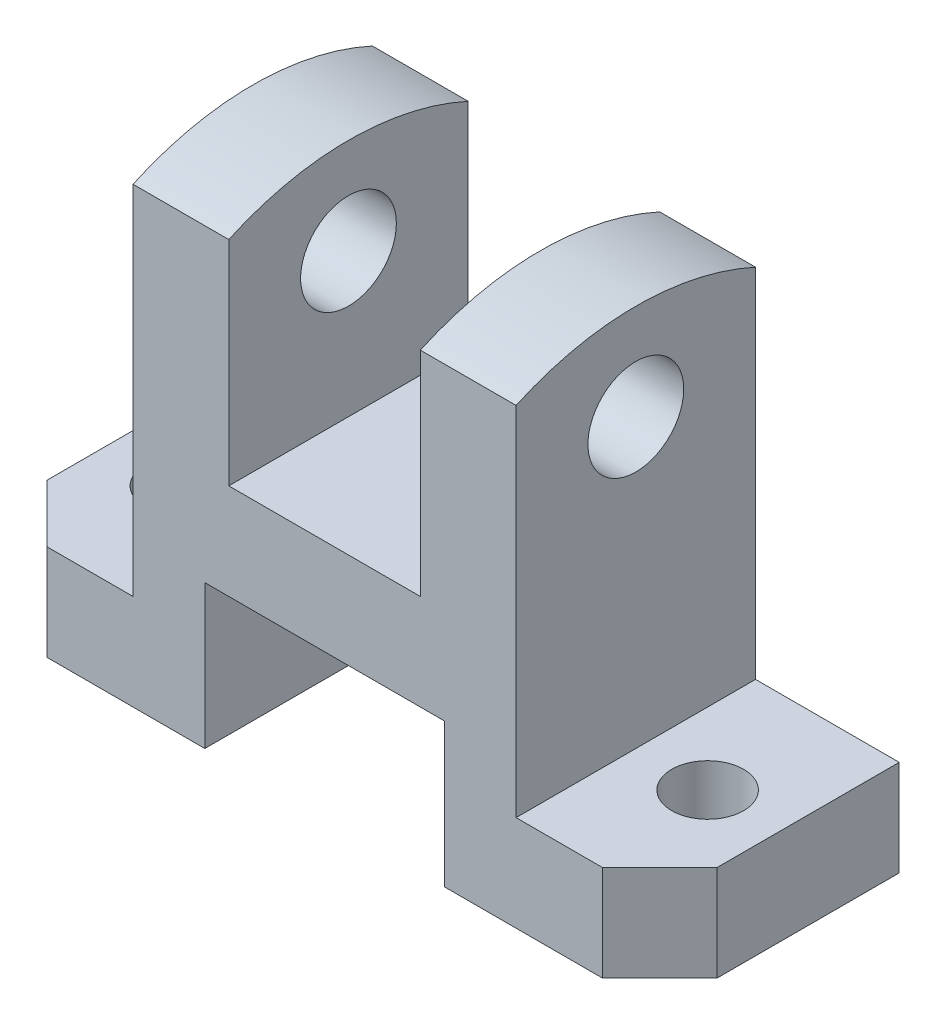
SolidWorks part; units mm, degrees
ref_plane "Front Plane" through (0, 0, 0) normal (0, 0, 1) x (1, 0, 0)
ref_plane "Top Plane" through (0, 0, 0) normal (0, 1, 0) x (1, 0, 0)
ref_plane "Right Plane" through (0, 0, 0) normal (1, 0, 0) x (0, 0, -1)
sketch "Sketch1" plane through (0, 0, 0) normal (0, 0, 1) x (1, 0, 0)
  line L1 (0, 0) -> (-9.525, 0)
  line L2 (0, 0) -> (0, -63.5)
  line L3 (0, -63.5) -> (-9.525, -63.5)
  line L4 (-9.525, 0) -> (-9.525, -63.5)
  line L5 (0, -31.75) -> (31.75, -31.75)
  line L6 (0, -31.75) -> (0, -44.45)
  line L7 (0, -44.45) -> (31.75, -44.45)
  line L8 (31.75, -31.75) -> (31.75, -44.45)
  line L9 (31.75, -63.5) -> (41.275, -63.5)
  line L10 (31.75, -63.5) -> (31.75, 0)
  line L11 (31.75, 0) -> (41.275, 0)
  line L12 (41.275, -63.5) -> (41.275, 0)
  line L13 (-9.525, -63.5) -> (-28.575, -63.5)
  line L14 (-9.525, -63.5) -> (-9.525, -50.8)
  line L15 (-9.525, -50.8) -> (-28.575, -50.8)
  line L16 (-28.575, -63.5) -> (-28.575, -50.8)
  line L17 (41.275, -63.5) -> (60.325, -63.5)
  line L18 (41.275, -63.5) -> (41.275, -50.8)
  line L19 (41.275, -50.8) -> (60.325, -50.8)
  line L20 (60.325, -63.5) -> (60.325, -50.8)
  line L21 (0, 0) -> (3.175, 0)
  line L22 (0, 0) -> (0, -31.75)
  line L23 (0, -31.75) -> (3.175, -31.75)
  line L24 (3.175, 0) -> (3.175, -31.75)
  line L25 (31.75, 0) -> (28.575, 0)
  line L26 (31.75, 0) -> (31.75, -31.75)
  line L27 (31.75, -31.75) -> (28.575, -31.75)
  line L28 (28.575, 0) -> (28.575, -31.75)
  dimension "D1" = 31.75
  dimension "D2" = 19.05
  dimension "D3" = 12.7
  dimension "D4" = 50.8
  dimension "D5" = 0
  dimension "D6" = 25.4
  dimension "D7" = 12.7
  dimension "D8" = 19.05
  dimension "D9" = 88.9
extrude "Boss-Extrude1" add sketch "Sketch1" along normal blind 31.75 contours L16 L13 L4 L15 | L1 L4 L3 L2 | L24 L21 L2 L5 | L8 L5 L2 L7 | L25 L28 L5 L10 | L9 L12 L11 L10 L8 | L17 L20 L19 L12
sketch "Sketch2" plane through (0, -50.8, 0) normal (0, 1, 0) x (1, 0, 0)
  line L0 (-20.955, -31.75) -> (-28.575, -24.13)
  line L1 (-9.525, -31.75) -> (-28.575, -31.75) construction
  line L2 (-28.575, -31.75) -> (-28.575, 0) construction
  line L3 (52.705, -31.75) -> (60.325, -24.13)
  line L4 (41.275, -31.75) -> (60.325, -31.75) construction
  line L5 (60.325, -31.75) -> (60.325, 0) construction
  line L6 (52.705, -31.75) -> (60.325, -31.75)
  line L7 (60.325, -31.75) -> (60.325, -24.13)
  line L8 (-28.575, -24.13) -> (-28.575, -31.75)
  line L9 (-28.575, -31.75) -> (-20.955, -31.75)
  dimension "D1" = 7.62
  dimension "D2" = 7.62
  dimension "D3" = 7.62
  dimension "D4" = 7.62
extrude "Cut-Extrude1" cut sketch "Sketch2" against normal blind 31.75
sketch "Sketch3" plane through (0, -50.8, 0) normal (0, 1, 0) x (1, 0, 0)
  line L0 (15.875, -41.7175) -> (15.875, 15.9292) construction
  line L1 (-28.575, -24.13) -> (-28.575, 0) construction
  line L4 (-9.525, 0) -> (-28.575, 0) construction
  circle A0 centre (-19.05, -15.875) radius 4.7625
  circle A1 centre (50.8, -15.875) radius 4.7625
  dimension "D2" = 9.525
  dimension "D1" = 44.45
  dimension "D3" = 9.525
  dimension "D4" = 15.875
extrude "Cut-Extrude2" cut sketch "Sketch3" against normal blind 31.75
sketch "Sketch4" plane through (41.275, 0, 0) normal (1, 0, 0) x (0, 0, -1)
  line L0 (-24.13, -50.8) -> (0, -50.8) construction
  line L1 (-31.75, -50.8) -> (-31.75, 0) construction
  line L2 (0, -50.8) -> (0, 0) construction
  line L3 (-31.75, 0) -> (0, 0) construction
  line L5 (-31.75, 0) -> (0, 0)
  line L6 (-31.75, 0) -> (-31.75, -3.4648)
  line L8 (0, 0) -> (0, -3.4648)
  circle A0 centre (-15.875, -12.7) radius 6.35
  arc A1 (-31.75, -3.4648) -> (0, -3.4648) centre (-15.875, -38.1) cw
  line M5 (0, -50.8) -> (0, 0)
  line M6 (0, 0) -> (-31.75, 0)
  line M7 (-31.75, 0) -> (-31.75, -50.8)
  dimension "D3" = 12.7
  dimension "D4" = 38.1
  dimension "D1" = 38.1
  dimension "D2" = 15.875
extrude "Cut-Extrude3" cut sketch "Sketch4" against normal through all contours A0 | A1 M6 M5 | A1 L5 M7
